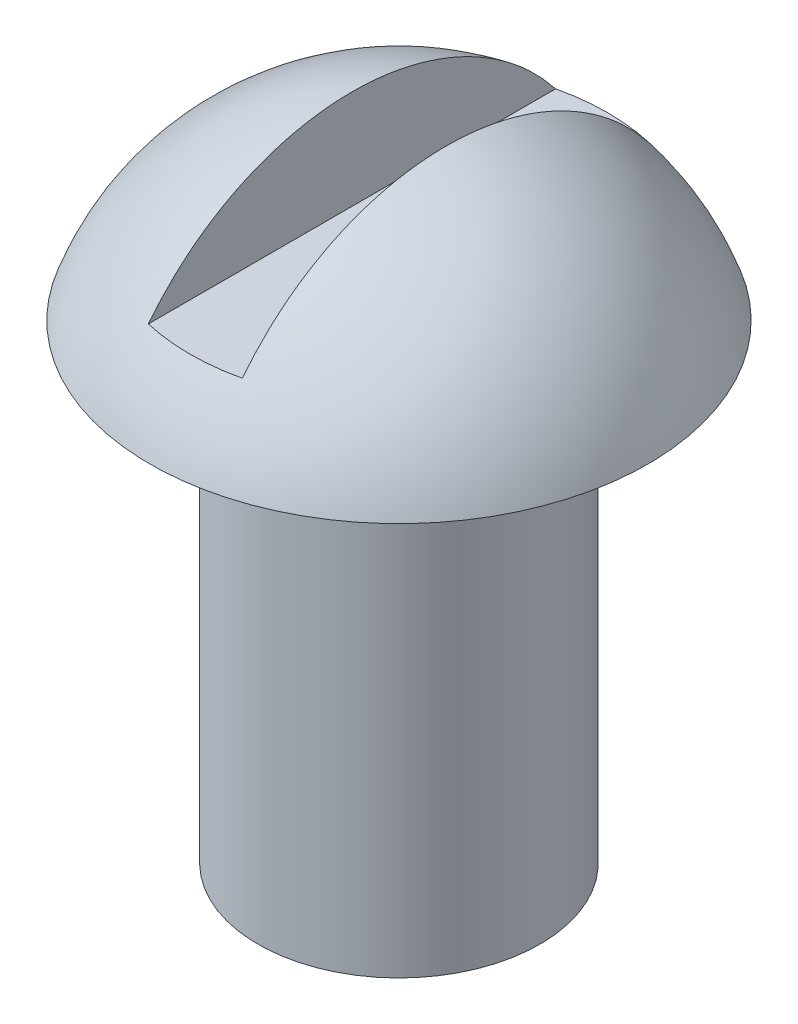
SolidWorks part; units mm, degrees
ref_plane "Спереди" through (0, 0, 0) normal (0, 0, 1) x (1, 0, 0)
ref_plane "Сверху" through (0, 0, 0) normal (0, 1, 0) x (1, 0, 0)
ref_plane "Справа" through (0, 0, 0) normal (1, 0, 0) x (0, 0, -1)
sketch "Эскиз1" plane through (0, 0, 0) normal (0, 0, 1) x (1, 0, 0)
  line L0 (0, 0) -> (2.65, 0)
  line L1 (0, 0) -> (0, 1.9) construction
  line L2 (0, 0) -> (0, 1.9)
  arc A0 (0, 1.9) -> (2.65, 0) centre (0, -0.898) cw
revolve "Повернуть1" add sketch "Эскиз1" angle 360 about L1
ref_plane "Плоскость1" through (0, 2, 0) normal (0, 1, 0) x (-1, 0, 0)
sketch "Эскиз2" plane through (0, 2, 0) normal (0, 1, 0) x (1, 0, 0)
  line L1 (-0.5, 2.9538) -> (0.5, 2.9538)
  line L2 (-0.5, 2.9538) -> (-0.5, -2.9538)
  line L3 (-0.5, -2.9538) -> (0.5, -2.9538)
  line L4 (0.5, 2.9538) -> (0.5, -2.9538)
  line L5 (-0.5, 2.9538) -> (0.5, -2.9538) construction
  line L6 (-0.5, -2.9538) -> (0.5, 2.9538) construction
  point P0 (0, 0)
extrude "Вытянуть1" cut sketch "Эскиз2" against normal blind 1.2
sketch "Эскиз3" plane through (0, 0, 0) normal (0, -1, 0) x (1, 0, 0)
  circle A0 centre (0, 0) radius 1.5
extrude "Вытянуть2" add sketch "Эскиз3" along normal blind 5
